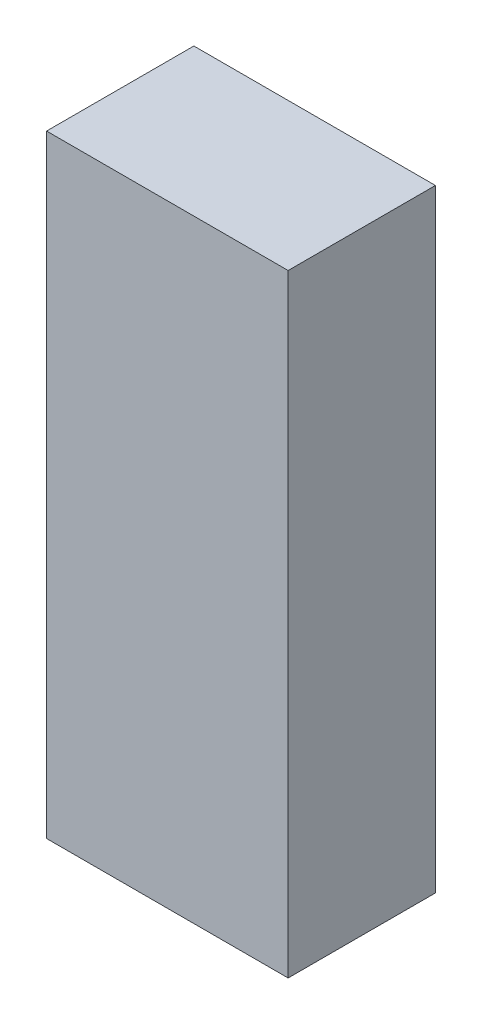
SolidWorks part; units mm, degrees
ref_plane "前视基准面" through (0, 0, 0) normal (0, 0, 1) x (1, 0, 0)
ref_plane "上视基准面" through (0, 0, 0) normal (0, 1, 0) x (1, 0, 0)
ref_plane "右视基准面" through (0, 0, 0) normal (1, 0, 0) x (0, 0, -1)
sketch "草图1" plane through (0, 0, 0) normal (0, 0, 1) x (1, 0, 0)
  line L0 (1.025, -2.6) -> (1.025, 2.6)
  line L1 (1.025, 2.6) -> (-1.025, 2.6)
  line L2 (-1.025, 2.6) -> (-1.025, -2.6)
  line L3 (-1.025, -2.6) -> (1.025, -2.6)
extrude "Component_Outline" add sketch "草图1" along normal blind 1.25 separate body
sketch3d "3D草图1"
  line L0 (0, 0, 0) -> (1, 0, 0)
  line L1 (0, 0, 0) -> (0, 1, 0)
  line L2 (0, 0, 0) -> (0, 0, 1)
  point P0 (0, 0, 0)
